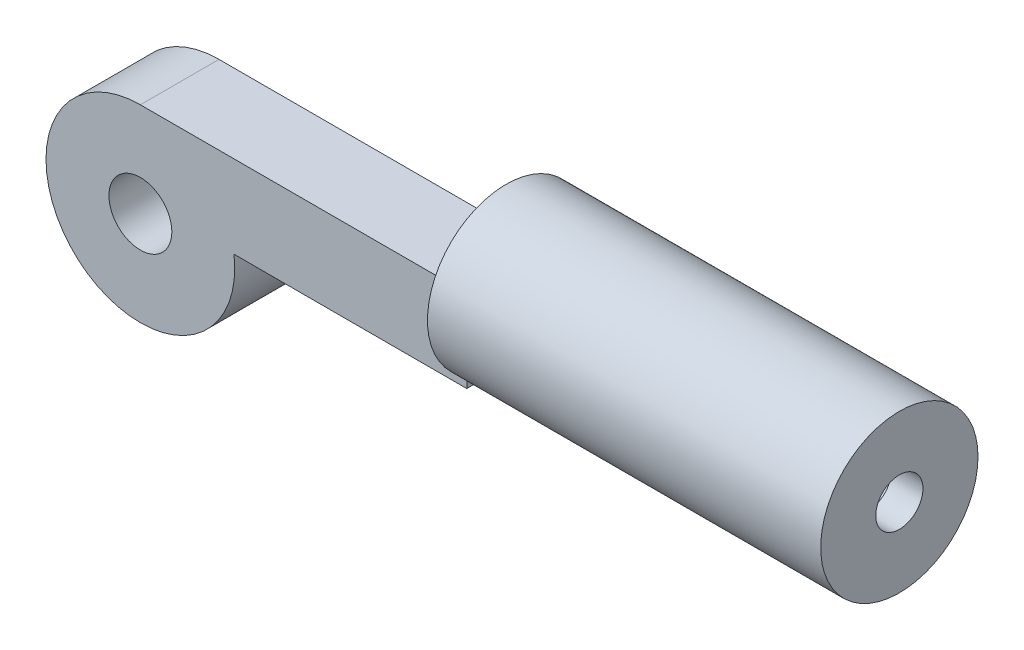
SolidWorks part; units mm, degrees
ref_plane "Front Plane" through (0, 0, 0) normal (0, 0, 1) x (1, 0, 0)
ref_plane "Top Plane" through (0, 0, 0) normal (0, 1, 0) x (1, 0, 0)
ref_plane "Right Plane" through (0, 0, 0) normal (1, 0, 0) x (0, 0, -1)
sketch "Sketch1" plane through (0, 0, 0) normal (0, 0, 1) x (1, 0, 0)
  circle A2 centre (0, 0) radius 120
extrude "Boss-Extrude2" add sketch "Sketch1" along normal blind 100 contours A2
sketch "Sketch2" plane through (0, 0, 100) normal (0, 0, 1) x (1, 0, 0)
  circle A0 centre (0, 0) radius 40
extrude "Cut-Extrude1" cut sketch "Sketch2" against normal blind 100
ref_plane "Plane1" through (915, 0, 0) normal (1, 0, 0) x (0, 0, -1)
sketch "Sketch3" plane through (915, 0, 0) normal (1, 0, 0) x (0, 0, -1)
  circle A0 centre (-50, 115) radius 100
extrude "Boss-Extrude3" add sketch "Sketch3" against normal blind 500 separate body contours A0
sketch "Sketch4" plane through (415, 0, 0) normal (-1, 0, 0) x (0, 0, 1)
  line L0 (0, 120) -> (0, -120) construction
  line L5 (0, 15) -> (100, 15)
  line L6 (0, 15) -> (0, 120)
  line L7 (0, 120) -> (100, 120)
  line L8 (100, 15) -> (100, 120)
extrude "Boss-Extrude4" add sketch "Sketch4" along normal up to surface (295.9412 mm away)
sketch "Sketch5" plane through (915, 0, 0) normal (1, 0, 0) x (0, 0, -1)
  circle A0 centre (-50, 115) radius 30
extrude "Cut-Extrude2" cut sketch "Sketch5" against normal blind 40
sketch "Sketch6" plane through (875, 0, 0) normal (1, 0, 0) x (0, 0, -1)
  circle A0 centre (-50, 115) radius 60
extrude "Cut-Extrude3" cut sketch "Sketch6" against normal blind 40
